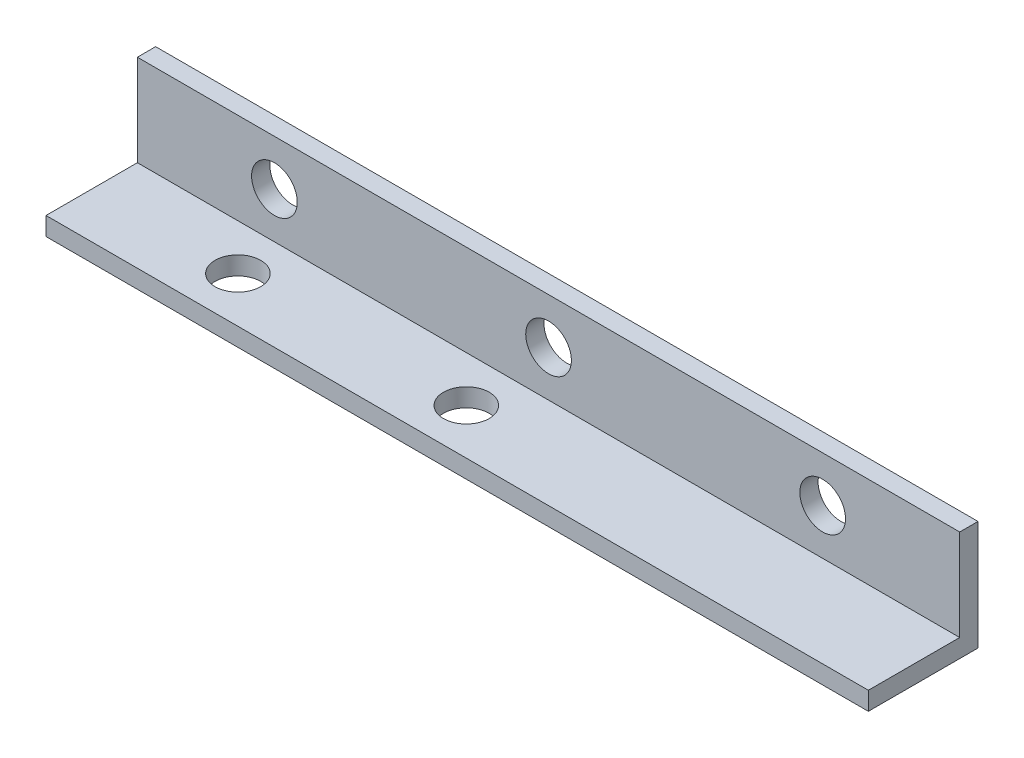
SolidWorks part; units mm, degrees
ref_plane "Front Plane" through (0, 0, 0) normal (0, 0, 1) x (1, 0, 0)
ref_plane "Top Plane" through (0, 0, 0) normal (0, 1, 0) x (1, 0, 0)
ref_plane "Right Plane" through (0, 0, 0) normal (1, 0, 0) x (0, 0, -1)
sketch "Sketch1" plane through (0, 0, 0) normal (0, 1, 0) x (1, 0, 0)
  line L1 (-61.1667, -4.5833) -> (28.8333, -4.5833)
  line L2 (-61.1667, -4.5833) -> (-61.1667, 7.4167)
  line L3 (-61.1667, 7.4167) -> (28.8333, 7.4167)
  line L4 (28.8333, -4.5833) -> (28.8333, 7.4167)
  line L5 (-61.1667, -4.5833) -> (28.8333, 7.4167) construction
  line L6 (-61.1667, 7.4167) -> (28.8333, -4.5833) construction
  point P0 (-16.1667, 1.4167)
  dimension "D1" = 12
  dimension "D2" = 90
extrude "Boss-Extrude1" add sketch "Sketch1" along normal blind 2
sketch "Sketch2" plane through (0, 2, 0) normal (0, 1, 0) x (1, 0, 0)
  line L0 (28.8333, -4.5833) -> (28.8333, 7.4167) construction
  line L1 (-61.1667, 7.4167) -> (28.8333, 7.4167)
  line L2 (-61.1667, 7.4167) -> (-61.1667, 5.4167)
  line L3 (-61.1667, 5.4167) -> (28.8333, 5.4167)
  line L4 (28.8333, 7.4167) -> (28.8333, 5.4167)
  dimension "2" = 2
extrude "Boss-Extrude2" add sketch "Sketch2" along normal blind 10
sketch "Sketch3" plane through (0, 2, 0) normal (0, 1, 0) x (1, 0, 0)
  line L0 (-61.1667, 7.4167) -> (-61.1667, -4.5833) construction
  line L4 (-61.1667, -4.5833) -> (28.8333, -4.5833) construction
  circle A0 centre (-45.1667, 0.4167) radius 2.5
  circle A1 centre (-20.1667, 0.4167) radius 2.5
  point P2 (0, 0)
  dimension "D1" = 5
  dimension "D2" = 5
  dimension "D3" = 25
  dimension "D4" = 16
  dimension "D5" = 5
  dimension "D6" = 5
extrude "Cut-Extrude1" cut sketch "Sketch3" against normal through all both and the other way through all
sketch "Sketch4" plane through (0, 0, -7.4167) normal (0, 0, -1) x (-1, 0, 0)
  line L0 (61.1667, 12) -> (61.1667, 0) construction
  line L1 (-28.8333, 12) -> (-28.8333, 0) construction
  line L2 (6.6, 0) -> (-6.6, 0) construction
  circle A0 centre (-13.8333, 7) radius 2.5
  circle A1 centre (16.1667, 7) radius 2.5
  circle A2 centre (46.1667, 7) radius 2.5
  dimension "D4" = 5
  dimension "D1" = 45
  dimension "D2" = 15
  dimension "D3" = 15
  dimension "7" = 7
  dimension "D6" = 7
  dimension "D7" = 7
extrude "Cut-Extrude2" cut sketch "Sketch4" against normal through all both and the other way through all
